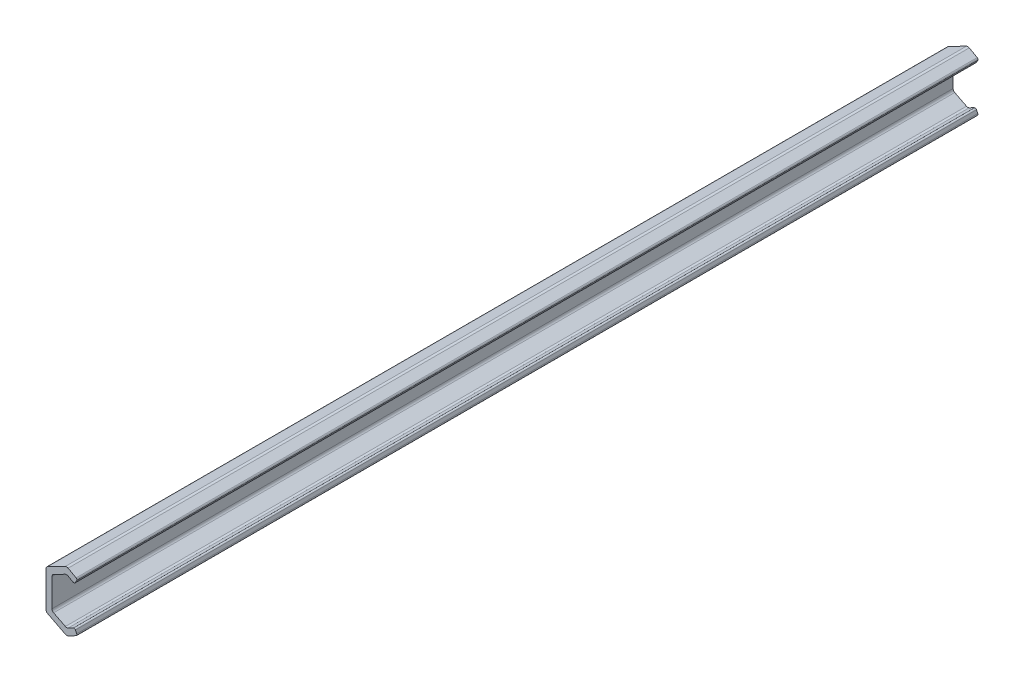
SolidWorks part; units mm, degrees
ref_plane "Front Plane" through (0, 0, 0) normal (0, 0, 1) x (1, 0, 0)
ref_plane "Top Plane" through (0, 0, 0) normal (0, 1, 0) x (1, 0, 0)
ref_plane "Right Plane" through (0, 0, 0) normal (1, 0, 0) x (0, 0, -1)
sketch "Sketch1" plane through (0, 0, 0) normal (0, 0, 1) x (1, 0, 0)
  line L0 (-91.2947, 32.4644) -> (-91.2947, 20.6949)
  line L1 (-90.7471, 19.8031) -> (-84.8447, 16.8091)
  line L2 (-83.94, 16.8091) -> (-81.2883, 18.1542)
  line L3 (-90.7471, 33.3563) -> (-84.865, 36.3399)
  line L4 (-83.9286, 36.3232) -> (-81.2799, 34.8582)
  line L5 (-83.9691, 34.0601) -> (-82.2479, 33.1081)
  line L6 (-88.7471, 32.1282) -> (-84.9055, 34.0768)
  line L7 (-89.2947, 31.2363) -> (-89.2947, 21.923)
  line L8 (-88.7471, 21.0312) -> (-84.8447, 19.0517)
  line L9 (-83.94, 19.0517) -> (-82.193, 19.9379)
  line L10 (-84.4329, 34.3165) -> (-81.8103, 32.8661) construction
  line L11 (-89.2947, 31.8504) -> (-84.4329, 34.3165) construction
  line L12 (-89.2947, 31.8504) -> (-89.2947, 21.309) construction
  line L13 (-89.2947, 21.309) -> (-84.3924, 18.8223) construction
  line L14 (-84.3924, 18.8223) -> (-81.7471, 20.164) construction
  line L15 (-91.2947, 20.0809) -> (-84.3924, 16.5797) construction
  line L16 (-84.3924, 16.5797) -> (-80.8424, 18.3804) construction
  line L17 (-91.2947, 33.0785) -> (-91.2947, 20.0809) construction
  line L18 (-91.2947, 33.0785) -> (-84.3924, 36.5797) construction
  line L19 (-84.3924, 36.5797) -> (-80.8424, 34.6162) construction
  line L20 (-81.0844, 34.1787) -> (-81.5684, 33.3036)
  line L21 (-81.0686, 18.8263) -> (-81.5209, 19.7181)
  arc A0 (-83.9691, 34.0601) -> (-84.9055, 34.0768) centre (-84.4531, 33.185) ccw
  arc A1 (-88.7471, 32.1282) -> (-89.2947, 31.2363) centre (-88.2947, 31.2363) ccw
  arc A2 (-89.2947, 21.923) -> (-88.7471, 21.0312) centre (-88.2947, 21.923) ccw
  arc A3 (-84.8447, 19.0517) -> (-83.94, 19.0517) centre (-84.3924, 19.9436) ccw
  arc A4 (-84.8447, 16.8091) -> (-83.94, 16.8091) centre (-84.3924, 17.701) ccw
  arc A5 (-91.2947, 20.6949) -> (-90.7471, 19.8031) centre (-90.2947, 20.6949) ccw
  arc A6 (-91.2947, 32.4644) -> (-90.7471, 33.3563) centre (-90.2947, 32.4644) cw
  arc A7 (-84.865, 36.3399) -> (-83.9286, 36.3232) centre (-84.4126, 35.4481) cw
  arc A8 (-82.193, 19.9379) -> (-81.5209, 19.7181) centre (-81.9668, 19.4919) cw
  arc A9 (-81.2883, 18.1542) -> (-81.0686, 18.8263) centre (-81.5145, 18.6001) ccw
  arc A10 (-82.2479, 33.1081) -> (-81.5684, 33.3036) centre (-82.0059, 33.5456) ccw
  arc A11 (-81.2799, 34.8582) -> (-81.0844, 34.1787) centre (-81.5219, 34.4207) cw
  point P27 (-84.3924, 16.5797)
  point P50 (-84.3947, 36.4479)
  dimension "D10" = 1
  dimension "D2" = 0.5
  dimension "D3" = 0.5
  dimension "D4" = 6.9
  dimension "D7" = 2
extrude "Boss-Extrude1" add sketch "Sketch1" along normal blind 300 contours L7 A2 L8 A3 L9 A8 L21 A9 L2 A4 L1 A5 L0 A6 L3 A7 L4 A11 L20 A10 L5 A0 L6 A1
